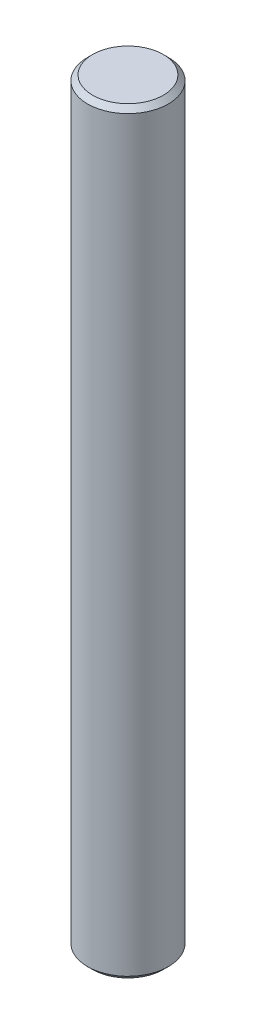
SolidWorks part; units mm, degrees
ref_plane "Front Plane" through (0, 0, 0) normal (0, 0, 1) x (1, 0, 0)
ref_plane "Top Plane" through (0, 0, 0) normal (0, 1, 0) x (1, 0, 0)
ref_plane "Right Plane" through (0, 0, 0) normal (1, 0, 0) x (0, 0, -1)
sketch "Sketch1" plane through (0, 0, 0) normal (0, 1, 0) x (1, 0, 0)
  circle A0 centre (0, 0) radius 4
  dimension "D1" = 8
extrude "Boss-Extrude1" add sketch "Sketch1" along normal mid plane 75
chamfer "Chamfer1" distance 0.5 angle 45 2 edges at (0, -37.5, 4) (0, 37.5, 4)
